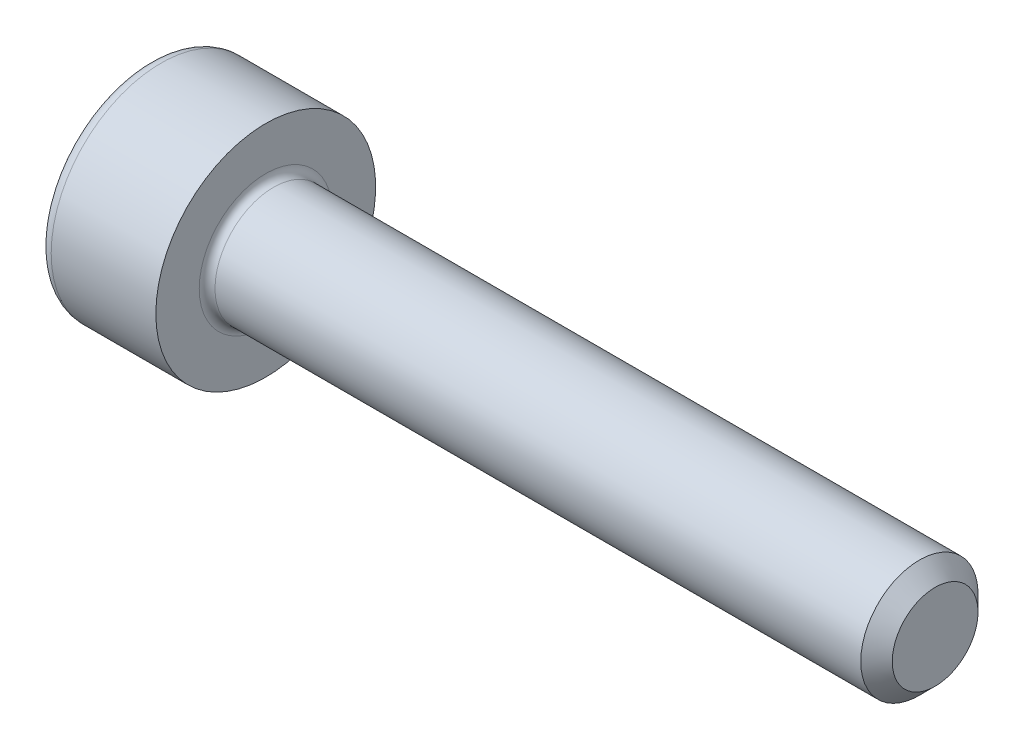
SolidWorks part; units mm, degrees
ref_plane "Спереди" through (0, 0, 0) normal (0, 0, 1) x (1, 0, 0)
ref_plane "Сверху" through (0, 0, 0) normal (0, 1, 0) x (1, 0, 0)
ref_plane "Справа" through (0, 0, 0) normal (1, 0, 0) x (0, 0, -1)
sketch "Sketch1" plane through (0, 0, 0) normal (0, 0, 1) x (1, 0, 0)
  line L0 (0, 0) -> (1.4887, 0)
  line L1 (1.4887, 0) -> (1.4887, 1.3957)
  line L2 (1.4887, 1.3957) -> (0, 1.3957)
  line L3 (0, 1.3957) -> (0, 0)
  line L4 (1.4887, 0) -> (9.9887, 0)
  line L5 (9.9887, 0) -> (9.9887, 0.7444)
  line L6 (9.9887, 0.7444) -> (1.4887, 0.7444)
  dimension "D1" = 8.5
revolve "Revolve1" add sketch "Sketch1" angle 360 about L0
fillet "Fillet1" radius 0.1 1 edges at (1.4887, 0, 0.7444)
fillet "Fillet2" radius 0.16 1 edges at (0, 0, 1.3957)
chamfer "Chamfer1" distance 0.2 angle 45 1 edges at (9.9887, 0, 0.7444)
sketch "Sketch2" plane through (0, 0, 0) normal (-1, 0, 0) x (0, 0, 1)
  line L1 (0, 0.8776) -> (-0.76, 0.4388)
  line L2 (-0.76, 0.4388) -> (-0.76, -0.4388)
  line L3 (-0.76, -0.4388) -> (0, -0.8776)
  line L4 (0, -0.8776) -> (0.76, -0.4388)
  line L5 (0.76, -0.4388) -> (0.76, 0.4388)
  line L6 (0.76, 0.4388) -> (0, 0.8776)
  circle A0 centre (0, 0) radius 0.76 construction
extrude "Extrude1" cut sketch "Sketch2" against normal blind 0.7
